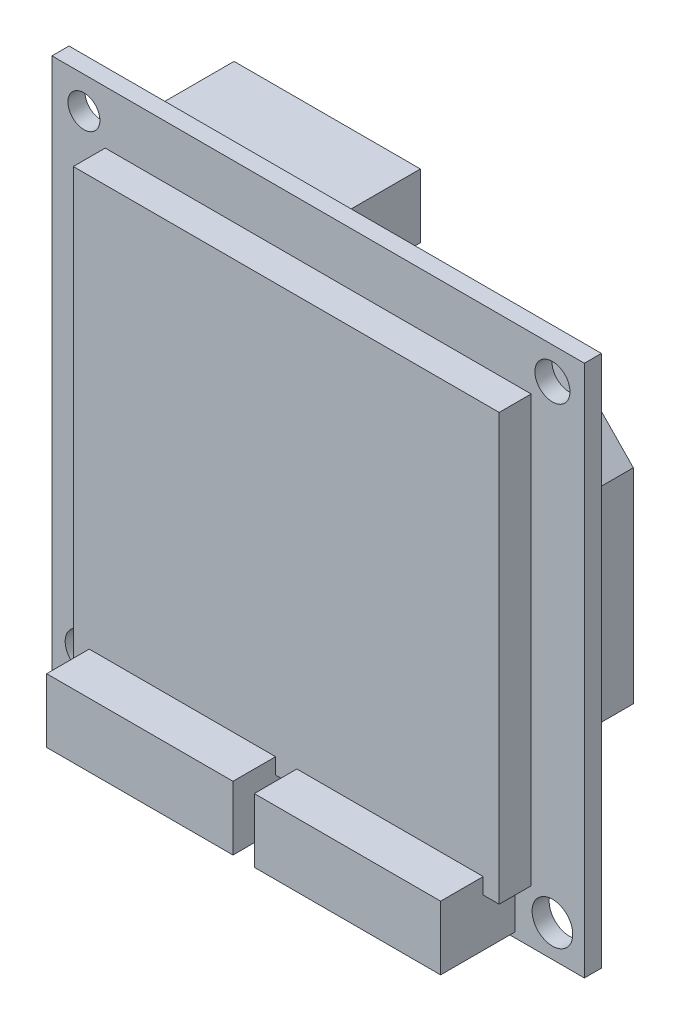
SolidWorks part; units mm, degrees
ref_plane "Front Plane" through (0, 0, 0) normal (0, 0, 1) x (1, 0, 0)
ref_plane "Top Plane" through (0, 0, 0) normal (0, 1, 0) x (1, 0, 0)
ref_plane "Right Plane" through (0, 0, 0) normal (1, 0, 0) x (0, 0, -1)
sketch "Sketch1" plane through (0, 0, 0) normal (0, 0, 1) x (1, 0, 0)
  line L0 (-25, 25) -> (25, 25)
  line L1 (25, 25) -> (25, -25)
  line L2 (25, -25) -> (-25, -25)
  line L3 (-25, -25) -> (-25, 25)
  line L4 (-25, 25) -> (25, -25)
  circle A0 centre (-22, 22) radius 1.5
  circle A1 centre (22, 22) radius 1.6469
  circle A2 centre (22, -22) radius 1.9082
  circle A3 centre (-22, -22) radius 1.7591
  dimension "D3" = 3
  dimension "D1" = 50
  dimension "D2" = 50
  dimension "D4" = 3
  dimension "D5" = 3
  dimension "D6" = 3
  dimension "D7" = 3
extrude "Extrude2" add sketch "Sketch1" along normal mid plane 1.6 contours L0 L4 L1 | L4 L3 L2
sketch "Sketch2" plane through (0, 0, 0.8) normal (0, 0, 1) x (1, 0, 0)
  line L0 (-20, 20) -> (20, 20)
  line L1 (20, 20) -> (20, -20)
  line L2 (20, -20) -> (-20, -20)
  line L3 (-20, -20) -> (-20, 20)
  line L4 (25, 25) -> (25, -25) construction
  line L5 (-25, -25) -> (-25, 25) construction
  line L6 (-25, 25) -> (25, 25) construction
  line L7 (25, -25) -> (-25, -25) construction
  line L8 (-20, 20) -> (20, -20)
  dimension "D1" = 40
  dimension "D2" = 40
extrude "Extrude3" add sketch "Sketch2" along normal blind 3 contours L8 L3 L2 | L0 L8 L1
sketch "Sketch3" plane through (0, 0, -0.8) normal (0, 0, -1) x (-1, 0, 0)
  line L0 (-20, -10) -> (-20, 9.2)
  line L1 (-20, 9.2) -> (-12.4, 17)
  line L2 (-12.4, 17) -> (-3.6, 17)
  line L3 (-3.6, 17) -> (4, 9.2)
  line L4 (4, 9.2) -> (4, -10)
  line L5 (4, -10) -> (-20, -10)
  line L6 (25, 25) -> (-25, 25) construction
  line L7 (-25, 25) -> (-25, -25) construction
  dimension "D1" = 27
  dimension "D2" = 24
  dimension "D3" = 7.8
  dimension "D4" = 7.6
  dimension "D5" = 8
  dimension "D6" = 5
extrude "Extrude4" add sketch "Sketch3" along normal blind 8
sketch "Sketch4" plane through (0, 0, 0.8) normal (0, 0, 1) x (1, 0, 0)
  line L0 (25, -25) -> (-25, -25) construction
  line L1 (18.5, -24.5) -> (1, -24.5)
  line L2 (18.5, -24.5) -> (18.5, -18.5)
  line L3 (18.5, -18.5) -> (1, -18.5)
  line L4 (1, -24.5) -> (1, -18.5)
  line L5 (-1, -24.5) -> (-18.5, -24.5)
  line L6 (-1, -24.5) -> (-1, -18.5)
  line L7 (-1, -18.5) -> (-18.5, -18.5)
  line L8 (-18.5, -24.5) -> (-18.5, -18.5)
  line L9 (25, 25) -> (25, -25) construction
  line L10 (-25, -25) -> (-25, 25) construction
  dimension "D1" = 17.5
  dimension "D2" = 6
  dimension "D3" = 0.5
  dimension "D4" = 6.5
  dimension "D5" = 6.5
extrude "Extrude6" add sketch "Sketch4" along normal blind 7
sketch "Sketch5" plane through (0, 0, -0.8) normal (0, 0, -1) x (-1, 0, 0)
  line L0 (25, 25) -> (-25, 25) construction
  line L1 (-1, 24.5) -> (16.5, 24.5)
  line L2 (-1, 24.5) -> (-1, 18.5)
  line L3 (-1, 18.5) -> (16.5, 18.5)
  line L4 (16.5, 24.5) -> (16.5, 18.5)
  line L5 (25, -25) -> (25, 25) construction
  dimension "D1" = 17.5
  dimension "D2" = 6
  dimension "D3" = 0.5
  dimension "D4" = 8.5
extrude "Extrude7" add sketch "Sketch5" along normal blind 7
